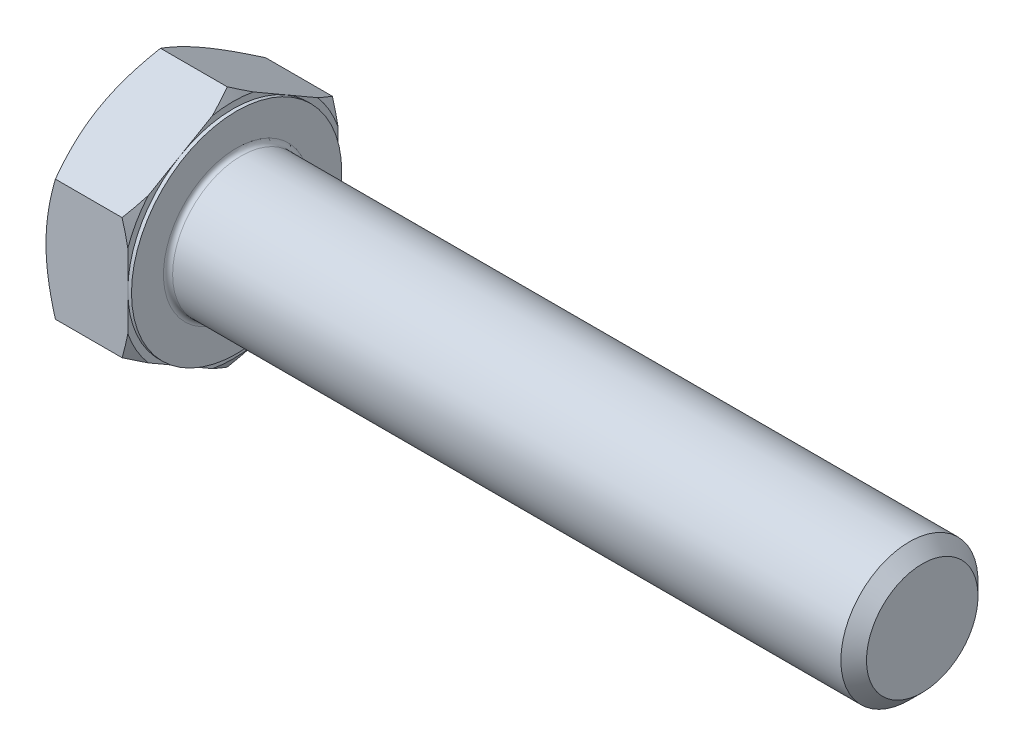
SolidWorks part; units mm, degrees
extrude "基体-拉伸" add sketch "草图1" along normal blind 18.7
sketch "草图1" plane through (0, 0, 0) normal (1, 0, 0) x (0, 0, -1)
  line L0 (23, 13.2791) -> (23, -13.2791)
  line L1 (-23, 13.2791) -> (-23, -13.2791)
  line L2 (23, -13.2791) -> (0, -26.5581)
  line L3 (0, -26.5581) -> (-23, -13.2791)
  line L4 (23, 13.2791) -> (0, 26.5581)
  line L5 (0, 26.5581) -> (-23, 13.2791)
  dimension "s" = 46
  dimension "D2" = 120
  dimension "D3" = 23
  dimension "D4" = 23
  dimension "D5" = 23
revolve "切除-旋转1" cut sketch "草图3" angle 360 about L6
sketch "草图3" plane through (0, 0, 0) normal (0, 0, 1) x (1, 0, 0)
  line L0 (0, 23) -> (4.941, 31.5581)
  line L1 (0, 26.5581) -> (0, 13.2791) construction
  line L2 (4.941, 31.5581) -> (4.941, 36.5581)
  line L3 (4.941, 36.5581) -> (-10, 36.5581)
  line L4 (-10, 36.5581) -> (-10, 23)
  line L5 (-10, 23) -> (0, 23)
  line L6 (0, 0) -> (99.06, 0) construction
  line L7 (18.7, 26.5581) -> (0, 26.5581) construction
  dimension "D1" = 23
  dimension "D2" = 5
  dimension "D3" = 10
  dimension "D4" = 5
  dimension "Head_ch_ang" = 30
ref_plane "前视" through (0, 0, 0) normal (0, 0, 1) x (1, 0, 0)
ref_plane "上视" through (0, 0, 0) normal (0, 1, 0) x (1, 0, 0)
ref_plane "右视" through (0, 0, 0) normal (1, 0, 0) x (0, 0, -1)
sketch "草图2" plane through (0, 0, 0) normal (0, 0, 1) x (1, 0, 0)
  line L0 (0, 13.2791) -> (0, -13.2791) construction
  line L1 (0, 0) -> (168.7, 0)
  line L2 (0, 0) -> (0, 15)
  line L3 (0, 15) -> (27.8072, 15)
  line L4 (168.7, 0) -> (168.7, 11.969)
  line L5 (18.7, 26.5581) -> (18.7, 13.2791) construction
  line L7 (0, 0) -> (96.52, 0) construction
  line L8 (168.7, -11.969) -> (27.8072, -15) construction
  line L9 (0, -15) -> (27.8072, -15) construction
  line L10 (22.2, 15.24) -> (22.2, -1.27) construction
  line L11 (96.7, 15.24) -> (96.7, -1.27) construction
  line L12 (18.7, 13.2791) -> (18.7, -13.2791) construction
  line L13 (27.8072, 15) -> (168.7, 15)
  line L14 (168.7, 15) -> (168.7, 11.969)
revolve "凸台-旋转1" add sketch "草图2" angle 360 about L7
cosmetic thread "螺旋线1" parameters "Thread_length"=72, "Thread_minor"=23.938
sketch "草图5" plane through (0, 0, 0) normal (0, 0, 1) x (1, 0, 0)
  line L0 (18.7, 23) -> (13.759, 31.5581)
  line L1 (18.7, 26.5581) -> (18.7, 13.2791) construction
  line L2 (13.759, 31.5581) -> (13.759, 36.5581)
  line L3 (13.759, 36.5581) -> (23.759, 36.5581)
  line L4 (23.759, 36.5581) -> (23.759, 23)
  line L5 (23.759, 23) -> (18.7, 23)
  line L7 (18.7, 26.5581) -> (2.0543, 26.5581) construction
  line L8 (0, 0) -> (99.06, 0) construction
  line L9 (0, 0) -> (99.06, 0) construction
  dimension "D1" = 23
  dimension "D2" = 5
  dimension "D3" = 10
  dimension "D4" = 5
revolve "切除-旋转2" cut sketch "草图5" angle 360 about L8
sketch "草图4" plane through (0, 0, 0) normal (0, 0, 1) x (1, 0, 0)
  line L1 (18.7, 26.5581) -> (18.7, 13.2791) construction
  line L2 (18.7, 23) -> (17.9, 23)
  line L3 (18.7, 23) -> (18.7, 36.5581)
  line L4 (18.7, 36.5581) -> (17.9, 36.5581)
  line L5 (0, 0) -> (95.25, 0) construction
  line L6 (0, 0) -> (96.52, 0) construction
  line L7 (17.9, 23) -> (17.9, 36.5581)
  line L8 (16.6457, 26.5581) -> (2.0543, 26.5581) construction
  dimension "D2" = 10
  dimension "D1" = 46
revolve "切除-旋转3" cut sketch "草图4" angle 360 about L5
chamfer "倒角" distance 2.8 angle 45 1 edges at (168.7, 0, 15)
fillet "圆角" radius 1 1 edges at (18.7, 0, -15)
sketch "草图6" plane through (0, 0, 0) normal (0, 0, 1) x (1, 0, 0)
  line L0 (96.7, -11.969) -> (94.9501, -15)
  line L1 (96.7, -11.969) -> (98.4499, -15)
  line L2 (98.4499, -15) -> (98.4499, -18.75)
  line L3 (-3.175, 0) -> (5.1513, 0) construction
  line L5 (98.4499, -18.75) -> (94.9501, -18.75)
  line L6 (94.9501, -18.75) -> (94.9501, -15)
  dimension "Thread_minor" = 23.938
  dimension "Diameter" = 30
  dimension "Start" = 96.7
revolve "切除-旋转4" [suppressed] cut sketch "草图6" angle 360 about L3
pattern_linear "阵列(线性)1" [suppressed]
equation "\"D3@草图1\" = \"s@草图1\" / 2"
equation "\"D4@草图1\" = \"D3@草图1\""
equation "\"D5@草图1\" = \"D4@草图1\""
equation "\"Thread_minor@螺旋线1\" = \"Minor_dia@草图2\""
equation "\"D1@草图3\" = \"s@草图1\" / 2"
equation "\"D1@草图5\" = \"s@草图1\" / 2"
equation "\"Head_ch_ang@草图5\" = \"Head_ch_ang@草图3\""
equation "\"D1@草图4\" = \"s@草图1\""
equation "\"Thread_length@螺旋线1\" = ((sgn( (\"l@草图2\" - \"p@草图2\" ) - \"h@草图2\" )-1)*( (\"l@草图2\" - \"p@草图2\" ) - \"h@草图2\" ))/-2+ \"h@草图2\""
equation "\"Thread_minor@草图6\" = \"Minor_dia@草图2\""
equation "\"Diameter@草图6\" = \"m@草图2\""
equation "\"Overcut@草图6\" = \"m@草图2\" * 1.25"
equation "\"Start@草图6\" = \"k@基体-拉伸\" + \"l@草图2\" - \"Thread_length@螺旋线1\"  '---Non-countersunk---"
equation "\"Num_threads@阵列(线性)1\" = int( \"Thread_length@螺旋线1\" / \"p@草图2\" + 0.999 )  + 1"
equation "\"Advance@阵列(线性)1\" = \"Thread_length@螺旋线1\" /  (\"Num_threads@阵列(线性)1\" - 1) 'relax it"
equation "\"Num_threads@阵列(线性)1\" = \"Num_threads@阵列(线性)1\" - sgn( \"Num_threads@阵列(线性)1\" - 1) '---chamfered tips only---"
equation "\"Minor_dia@草图2\" = \"m@草图2\"-\"p@草图2\" * 1.732"
equation "\"D1@倒角\" = \"p@草图2\"*0.8"
